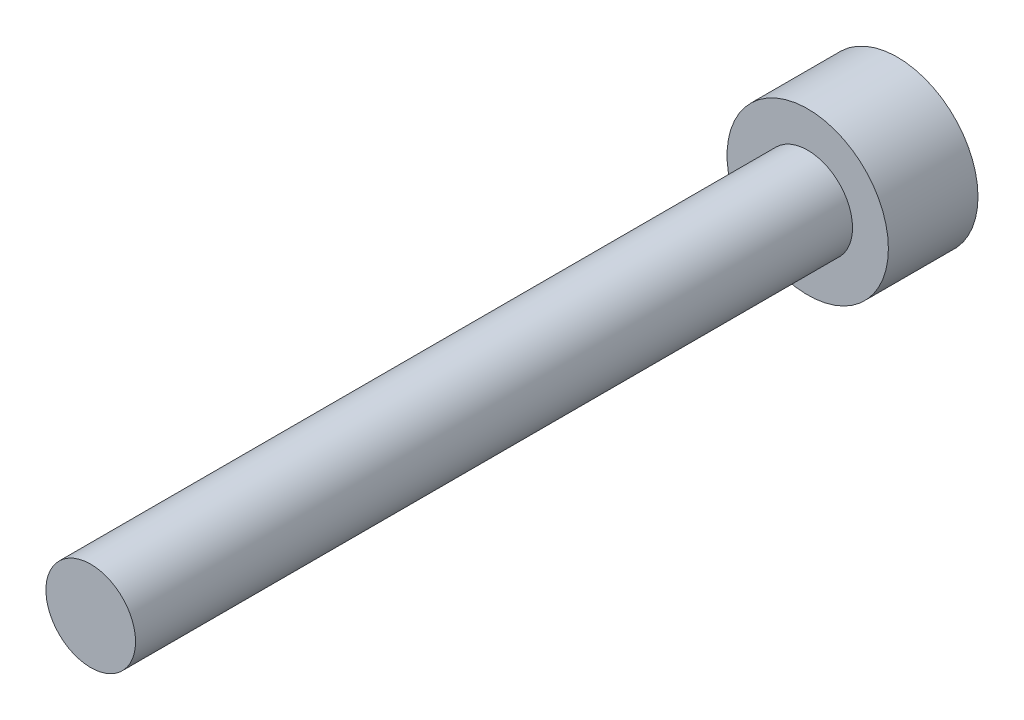
SolidWorks part; units mm, degrees
material "AISI 304"
ref_plane "Alzado" through (0, 0, 0) normal (0, 0, 1) x (1, 0, 0)
ref_plane "Planta" through (0, 0, 0) normal (0, 1, 0) x (1, 0, 0)
ref_plane "Vista lateral" through (0, 0, 0) normal (1, 0, 0) x (0, 0, -1)
sketch "Sk_Cabeza" plane through (0, 0, 0) normal (0, 0, 1) x (1, 0, 0)
  circle A0 centre (0, 0) radius 2.25
  dimension "D1" = 4.5
extrude "Cabeza" add sketch "Sk_Cabeza" along normal blind 2.5 from offset 2.5
sketch "Sk_Cuerpo" plane through (0, 0, 0) normal (0, 0, 1) x (1, 0, 0)
  circle A0 centre (0, 0) radius 1.25
  dimension "D1" = 2.5
extrude "Cuerpo" add sketch "Sk_Cuerpo" along normal blind 20
sketch "Sk_Hexagono_interior" plane through (0, 0, 0) normal (0, 0, 1) x (1, 0, 0)
  line L1 (0, -1.1547) -> (1, -0.5774)
  line L2 (1, -0.5774) -> (1, 0.5774)
  line L3 (1, 0.5774) -> (0, 1.1547)
  line L4 (0, 1.1547) -> (-1, 0.5774)
  line L5 (-1, 0.5774) -> (-1, -0.5774)
  line L6 (-1, -0.5774) -> (0, -1.1547)
  circle A0 centre (0, 0) radius 1 construction
  dimension "D1" = 2
extrude "Hexagono_interior" cut sketch "Sk_Hexagono_interior" along normal blind 1.25 from offset 2.5
